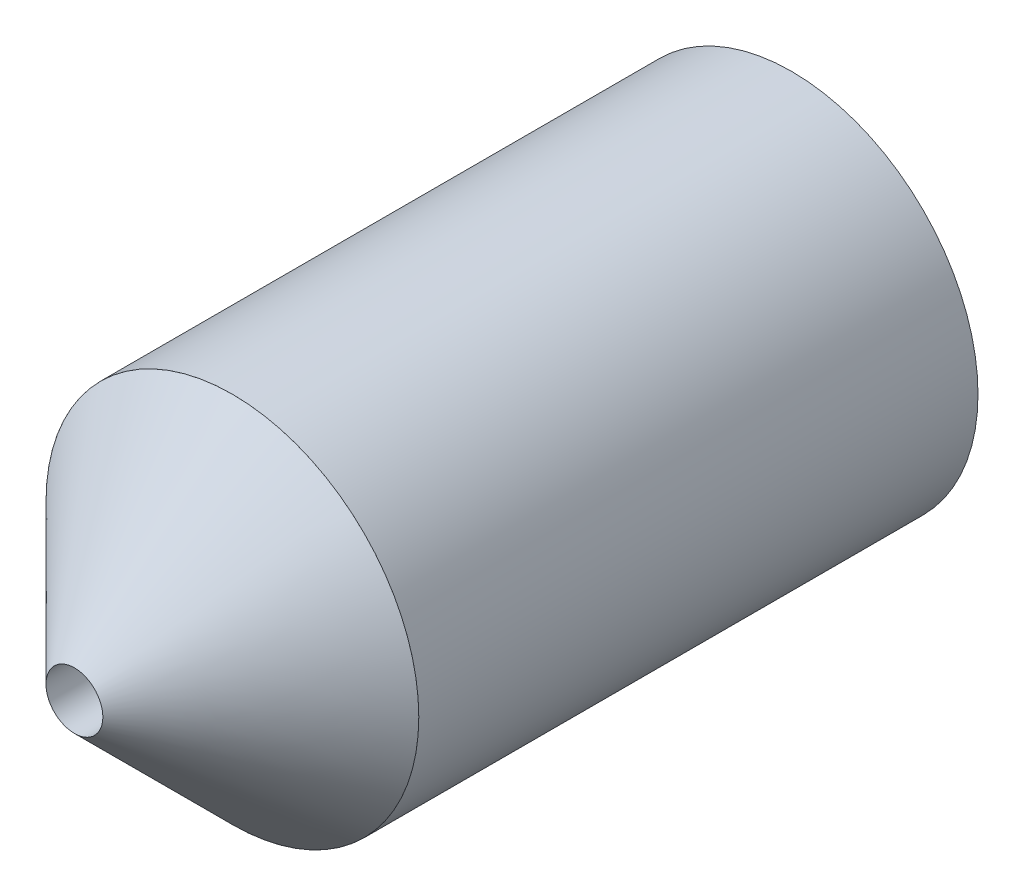
SolidWorks part; units mm, degrees
ref_plane "Front Plane" through (0, 0, 0) normal (0, 0, 1) x (1, 0, 0)
ref_plane "Top Plane" through (0, 0, 0) normal (0, 1, 0) x (1, 0, 0)
ref_plane "Right Plane" through (0, 0, 0) normal (1, 0, 0) x (0, 0, -1)
sketch "Sketch1" plane through (0, 0, 0) normal (0, 0, 1) x (1, 0, 0)
  circle A0 centre (0, 0) radius 20
  dimension "D1" = 40
extrude "Boss-Extrude1" add sketch "Sketch1" along normal blind 60
sketch "Sketch2" plane through (0, 0, 60) normal (0, 0, 1) x (1, 0, 0)
  circle A0 centre (0, 0) radius 3.05
  dimension "D1" = 6.1
extrude "Cut-Extrude1" cut sketch "Sketch2" against normal blind 30 contours A0
sketch "Sketch3" plane through (0, 0, 0) normal (0, 0, -1) x (-1, 0, 0)
  circle A0 centre (0, 0) radius 3.29
extrude "Cut-Extrude2" cut sketch "Sketch3" against normal blind 30
sketch3d "3DSketch3"
  line L0 (-0.2811, 19.998, 60) -> (0, 0, 60)
  line L1 (0, 0, 30) -> (0, 0, 60) construction
  line L2 (0, 0, 60) -> (0, 0, 0) construction
  line L3 (0, 0, 60) -> (0, 0, 80)
  line L4 (0, 0, 80) -> (-0.2811, 19.998, 60)
  circle A0 centre (0, 0, 60) radius 20 construction
  point P4 (0, 0, 80)
  dimension "D1" = 20
sketch "Sketch6" plane through (0, 0, 0) normal (1, 0, 0) x (0, 0, -1)
  line L0 (-60, 19.998) -> (-80, 0)
  line L1 (-80, 0) -> (-60, 0)
  line L2 (-60, 0) -> (-60, 19.998)
revolve "Revolve1" add sketch "Sketch6" angle 360 about L3
sketch "Sketch7" plane through (0, 0, 0) normal (0, 0, -1) x (-1, 0, 0)
  circle A0 centre (0, 0) radius 3.05
extrude "Cut-Extrude3" cut sketch "Sketch7" against normal blind 100
